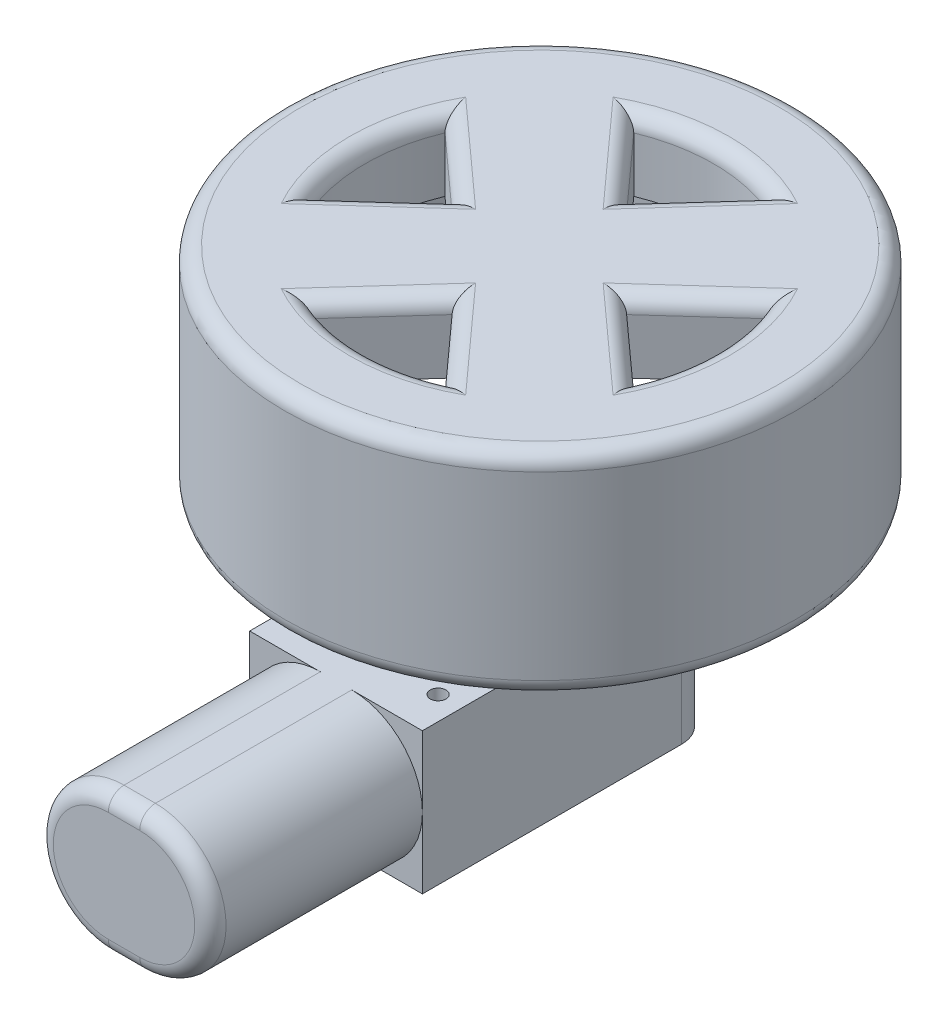
SolidWorks part; units mm, degrees
ref_plane "Front Plane" through (0, 0, 0) normal (0, 0, 1) x (1, 0, 0)
ref_plane "Top Plane" through (0, 0, 0) normal (0, 1, 0) x (1, 0, 0)
ref_plane "Right Plane" through (0, 0, 0) normal (1, 0, 0) x (0, 0, -1)
sketch "Sketch1" plane through (0, 0, 0) normal (0, 0, 1) x (1, 0, 0)
  line L1 (-11, 9) -> (11, 9)
  line L2 (-11, 9) -> (-11, -9)
  line L3 (-11, -9) -> (11, -9)
  line L4 (11, 9) -> (11, -9)
  line L5 (-11, 9) -> (11, -9) construction
  line L6 (-11, -9) -> (11, 9) construction
  point P0 (0, 0)
  dimension "D1" = 18
  dimension "D2" = 22
extrude "Boss-Extrude1" add sketch "Sketch1" along normal blind 64
sketch "Sketch2" plane through (0, 0, 64) normal (0, 0, 1) x (1, 0, 0)
  line L0 (-2, 0) -> (2, 0) construction
  line L1 (2, -9) -> (11, -9)
  line L2 (-2, 9) -> (-11, 9)
  line L3 (11, -9) -> (11, 9) construction
  line L4 (-11, 9) -> (-11, -9) construction
  line L5 (11, 9) -> (-11, 9) construction
  line L6 (-11, -9) -> (11, -9) construction
  line L7 (-11, 9) -> (-11, -9)
  line L8 (-11, -9) -> (-2, -9)
  line L9 (11, -9) -> (11, 9)
  line L10 (11, 9) -> (2, 9)
  arc A0 (-2, 9) -> (-2, -9) centre (-2, 0) ccw
  arc A1 (2, -9) -> (2, 9) centre (2, 0) ccw
  point P3 (0, 0)
  point P8 (0, 0)
  point P9 (2.0805, 0)
  point P10 (-2.0567, 0)
  point P11 (11, 0)
  point P14 (11, 0)
  point P15 (-11, 0)
  point P20 (0, 9)
  line M5 (11, -9) -> (11, 9)
  line M6 (11, 9) -> (-11, 9)
  line M7 (-11, 9) -> (-11, -9)
  line M8 (-11, -9) -> (11, -9)
extrude "Cut-Extrude1" cut sketch "Sketch2" against normal blind 27 contours A0 M6 M7 | A0 L7 M8 | A1 M8 M5 | A1 L9 M6
fillet "Fillet1" radius 4 2 edges at (11, 0, 0) (-11, 0, 0)
sketch "Sketch3" plane through (0, 9, 0) normal (0, 1, 0) x (1, 0, 0)
  line L0 (0, -1.5078) -> (0, -18.4947) construction
  circle A0 centre (0, -11) radius 2.5
  dimension "D1" = 5
  dimension "D2" = 11
extrude "Boss-Extrude2" add sketch "Sketch3" along normal blind 8
sketch "Sketch4" plane through (0, -9, 0) normal (0, -1, 0) x (1, 0, 0)
  line L0 (0, 31.9364) -> (0, 5.6038) construction
  circle A0 centre (0, 11) radius 2.5
  dimension "D1" = 5
  dimension "D2" = 11
extrude "Boss-Extrude3" add sketch "Sketch4" along normal blind 8
sketch "Sketch5" plane through (0, -9, 0) normal (0, -1, 0) x (1, 0, 0)
  line L0 (-16.5487, 32) -> (19.4694, 32) construction
  line L1 (11, 37) -> (2, 37) construction
  line L2 (11, 37) -> (11, 4) construction
  line L3 (-11, 37) -> (-11, 4) construction
  circle A0 centre (8, 32) radius 1
  circle A1 centre (-8, 32) radius 1
  dimension "D2" = 3
  dimension "D4" = 2
  dimension "D1" = 5
  dimension "D3" = 3
extrude "Cut-Extrude2" cut sketch "Sketch5" against normal up to next
fillet "Fillet2" radius 2 4 edges at (0, -9, 64) (-11, 0, 64) (0, 9, 64) (11, 0, 64)
sketch "Sketch7" plane through (0, 17, 0) normal (0, 1, 0) x (1, 0, 0)
  circle A0 centre (0, -11) radius 32.5
  dimension "D1" = 65
extrude "Boss-Extrude4" add sketch "Sketch7" along normal blind 27
sketch "Sketch8" plane through (0, 17, 0) normal (0, -1, 0) x (1, 0, 0)
  circle A0 centre (0, 11) radius 4
  circle A1 centre (0, 11) radius 26.3742
  dimension "D1" = 8
extrude "Cut-Extrude3" cut sketch "Sketch8" against normal blind 18
sketch "Sketch10" plane through (0, 44, 0) normal (0, 1, 0) x (1, 0, 0)
  line L0 (11.1058, -11.1058) -> (20.4969, -2.6293)
  line L1 (11.1058, -11.1058) -> (20.4969, -19.5824)
  line L2 (-11.1058, -11.1058) -> (-20.4969, -2.6293)
  line L3 (-11.1058, -11.1058) -> (-20.4969, -19.5824)
  line L4 (0, 0) -> (8.4765, 9.391)
  line L5 (0, 0) -> (-8.4765, 9.391)
  line L6 (0, -22.2117) -> (8.4765, -31.6027)
  line L7 (0, -22.2117) -> (-8.4765, -31.6027)
  arc A0 (-8.4765, -31.6027) -> (8.4765, -31.6027) centre (0, -11.1058) ccw
  arc A1 (20.4969, -19.5824) -> (20.4969, -2.6293) centre (0, -11.1058) ccw
  arc A2 (8.4765, 9.391) -> (-8.4765, 9.391) centre (0, -11.1058) ccw
  arc A3 (-20.4969, -2.6293) -> (-20.4969, -19.5824) centre (0, -11.1058) ccw
extrude "Cut-Extrude4" cut sketch "Sketch10" against normal up to next
fillet "Fillet3" radius 2 7 edges at (-22.1805, 44, 11.1058) (0, 44, 33.2863) (22.1805, 44, 11.1058) (0, 44, -11.0746) (0, 17, -15.3742) (0, 17, 43.5) (0, 44, 43.5)
fillet "Fillet4" radius 2 8 edges at (16.5853, 44, 6.16) (16.5853, 44, 16.0517) (4.9458, 44, 27.6911) (-4.9458, 44, 27.6911) (-16.5853, 44, 16.0517) (-16.5853, 44, 6.16) (-4.9458, 44, -5.4794) (4.9458, 44, -5.4794)
